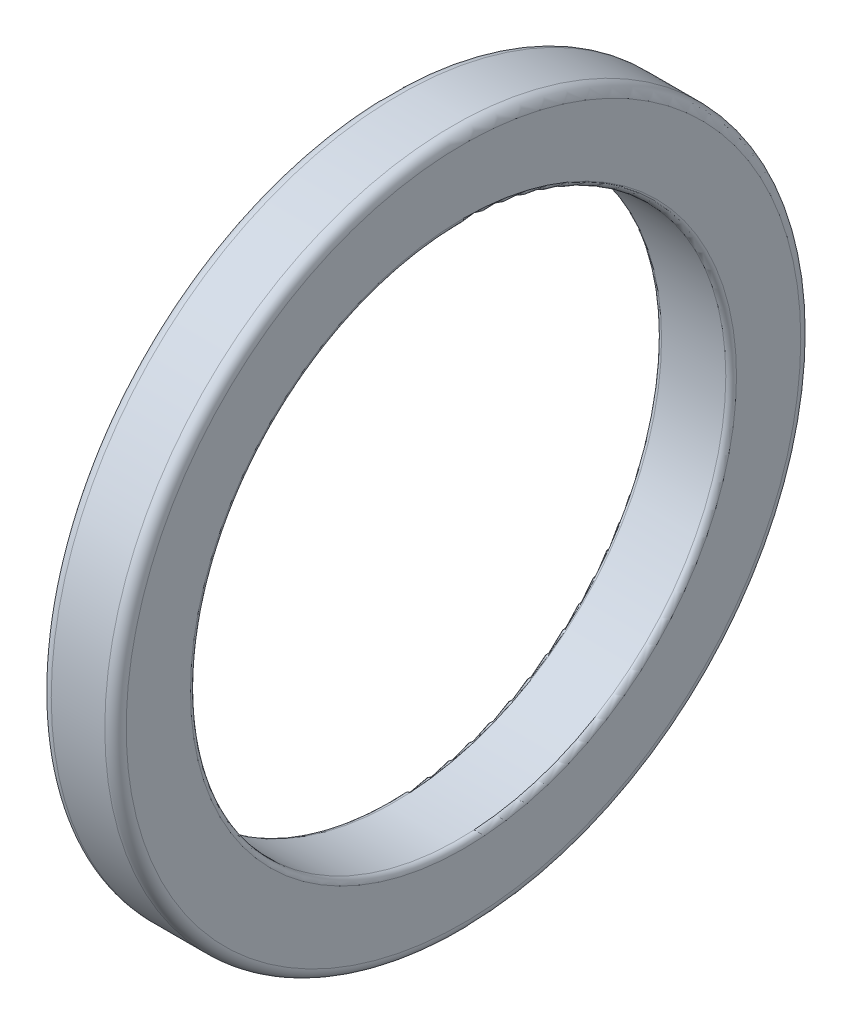
SolidWorks part; units mm, degrees
ref_plane "Front Plane" through (0, 0, 0) normal (0, 0, 1) x (1, 0, 0)
ref_plane "Top Plane" through (0, 0, 0) normal (0, 1, 0) x (1, 0, 0)
ref_plane "Right Plane" through (0, 0, 0) normal (1, 0, 0) x (0, 0, -1)
sketch "Sketch1" plane through (0, 0, 0) normal (1, 0, 0) x (0, 0, -1)
  circle A0 centre (0, 0) radius 32.5
  circle A1 centre (0, 0) radius 25
  dimension "D1" = 65
  dimension "D2" = 50
extrude "Boss-Extrude1" add sketch "Sketch1" along normal blind 7
fillet "Fillet1" radius 1 2 edges at (0, 0, -32.5) (7, 0, -32.5)
fillet "Fillet2" radius 0.5 2 edges at (7, 0, -25) (0, 0, -25)
